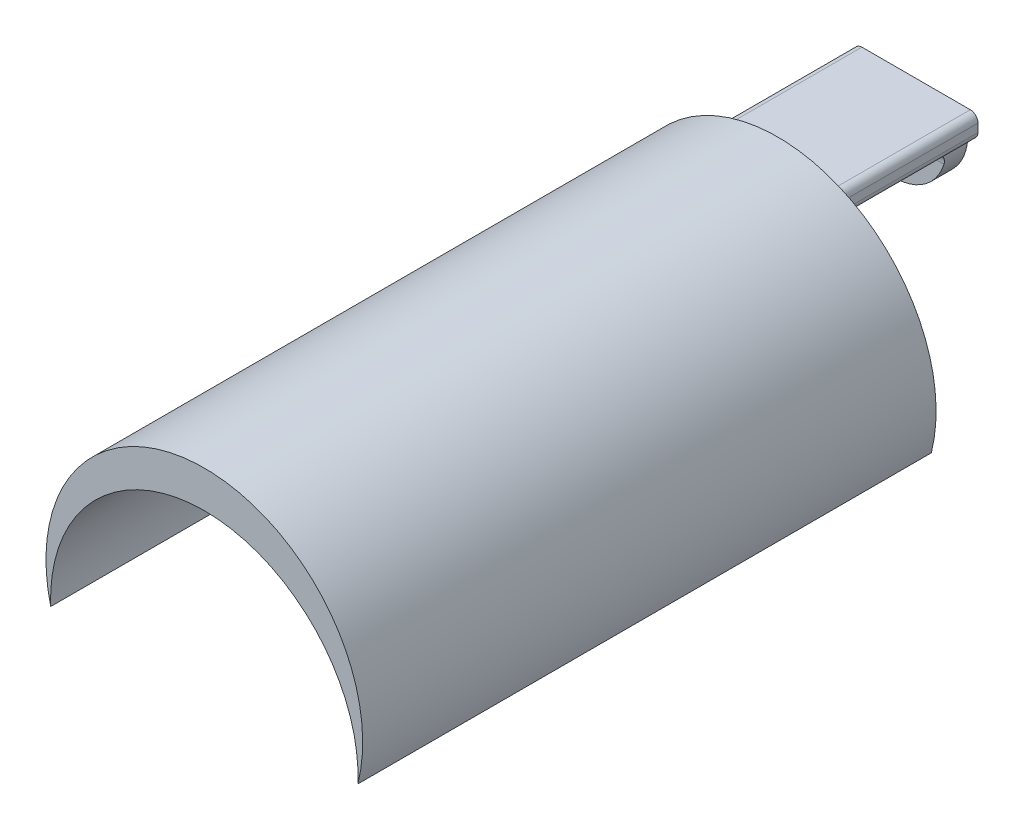
SolidWorks part; units mm, degrees
ref_plane "Front Plane" through (0, 0, 0) normal (0, 0, 1) x (1, 0, 0)
ref_plane "Top Plane" through (0, 0, 0) normal (0, 1, 0) x (1, 0, 0)
ref_plane "Right Plane" through (0, 0, 0) normal (1, 0, 0) x (0, 0, -1)
sketch "Sketch1" plane through (0, 0, 0) normal (0, 0, 1) x (1, 0, 0)
  circle A0 centre (0, 0) radius 26.162
  dimension "D1" = 52.324
extrude "Boss-Extrude1" add sketch "Sketch1" along normal blind 94.742
sketch "Sketch2" plane through (0, 0, 94.742) normal (0, 0, 1) x (1, 0, 0)
  circle A0 centre (0, -5.334) radius 25.4
  circle A1 centre (0, 0) radius 26.162 construction
  dimension "D1" = 5.334
  dimension "D2" = 50.8
extrude "Cut-Extrude1" cut sketch "Sketch2" against normal blind 35.052
sketch "Sketch3" plane through (0, 0, 59.69) normal (0, 0, 1) x (1, 0, 0)
  circle A0 centre (0, -3.3391) radius 20.066
  dimension "D1" = 40.132
extrude "Cut-Extrude2" cut sketch "Sketch3" against normal blind 134.62
sketch "Sketch6" plane through (0, 0, 0) normal (1, 0, 0) x (0, 0, -1)
  line L1 (-59.69, -6.35) -> (4.5299, -6.35)
  line L2 (-59.69, -6.35) -> (-59.69, -29.1996)
  line L3 (-59.69, -29.1996) -> (4.5299, -29.1996)
  line L4 (4.5299, -6.35) -> (4.5299, -29.1996)
extrude "Cut-Extrude4" cut sketch "Sketch6" against normal mid plane 67.818
sketch "Sketch11" plane through (0, 0, 0) normal (0, 0, -1) x (-1, 0, 0)
  line L0 (0, 0) -> (0, 28.9574) construction
  line L2 (-8.9579, 23.1051) -> (8.9579, 23.1051)
  line L3 (-10.2279, 21.8351) -> (-10.2279, 20.4735)
  line L4 (-8.9579, 19.2035) -> (8.9579, 19.2035)
  line L5 (10.2279, 21.8351) -> (10.2279, 20.4735)
  line L6 (-10.2279, 23.1051) -> (10.2279, 19.2035) construction
  line L7 (-10.2279, 19.2035) -> (10.2279, 23.1051) construction
  arc A0 (10.2279, 21.8351) -> (8.9579, 23.1051) centre (8.9579, 21.8351) ccw
  arc A1 (10.2279, 20.4735) -> (8.9579, 19.2035) centre (8.9579, 20.4735) cw
  arc A2 (-10.2279, 20.4735) -> (-8.9579, 19.2035) centre (-8.9579, 20.4735) ccw
  arc A3 (-10.2279, 21.8351) -> (-8.9579, 23.1051) centre (-8.9579, 21.8351) cw
  point P3 (0, 21.1543)
  dimension "D1" = 1.27
extrude "Boss-Extrude3" add sketch "Sketch11" along normal blind 22.86
sketch "Sketch12" plane through (0, 0, -22.86) normal (0, 0, -1) x (-1, 0, 0)
  line L1 (-8.9579, 19.2035) -> (8.9579, 19.2035) construction
  line L2 (-8.5396, 19.2035) -> (8.5396, 19.2035)
  arc A0 (-8.5396, 19.2035) -> (8.5396, 19.2035) centre (0, 19.2035) ccw
extrude "Boss-Extrude4" add sketch "Sketch12" against normal blind 3.556
fillet "Fillet3" radius 2.54 1 edges at (0, 19.2035, -19.304)
fillet "Fillet4" radius 0.254 2 edges at (8.5396, 19.2035, -19.812) (-8.5396, 19.2035, -19.812)
